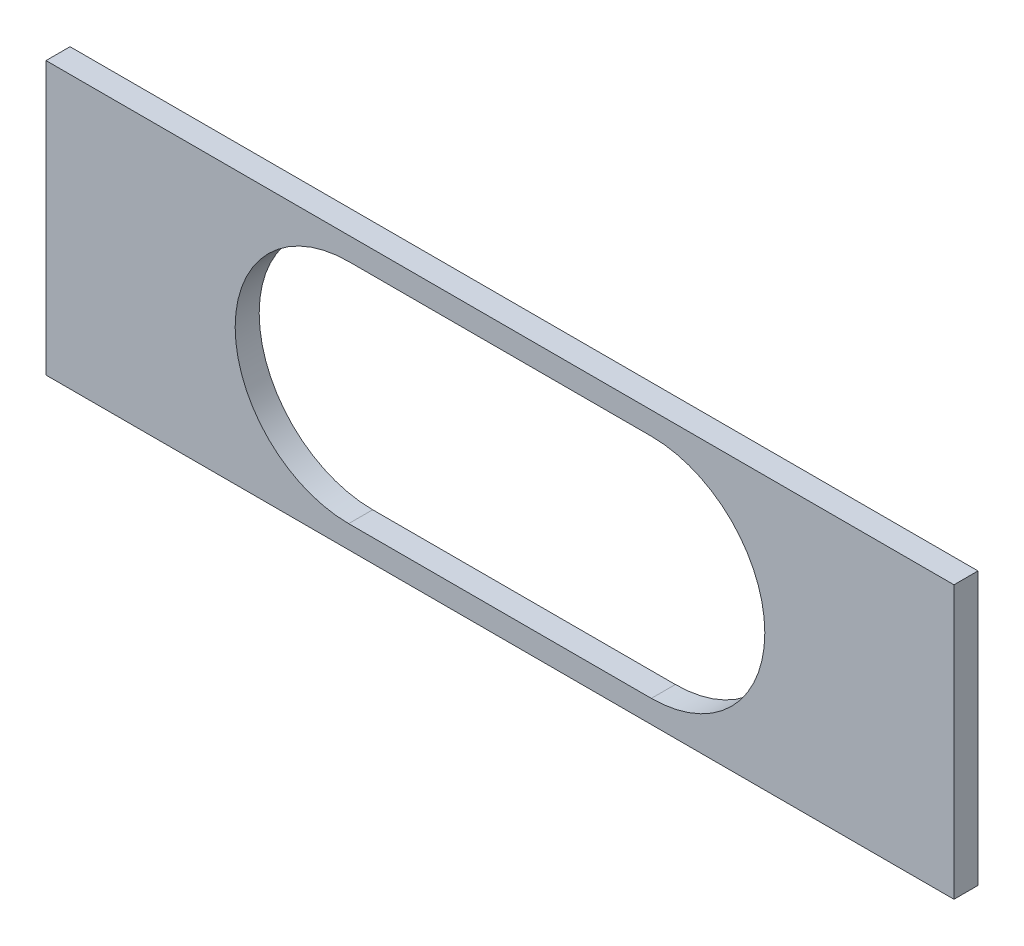
SolidWorks part; units mm, degrees
ref_plane "Front Plane" through (0, 0, 0) normal (0, 0, 1) x (1, 0, 0)
ref_plane "Top Plane" through (0, 0, 0) normal (0, 1, 0) x (1, 0, 0)
ref_plane "Right Plane" through (0, 0, 0) normal (1, 0, 0) x (0, 0, -1)
sketch "Sketch1" plane through (0, 0, 0) normal (0, 0, 1) x (1, 0, 0)
  line L1 (60, -18) -> (-60, -18)
  line L2 (60, -18) -> (60, 18)
  line L3 (60, 18) -> (-60, 18)
  line L4 (-60, -18) -> (-60, 18)
  line L5 (60, -18) -> (-60, 18) construction
  line L6 (60, 18) -> (-60, -18) construction
  point P0 (0, 0)
  dimension "D1" = 120
  dimension "D2" = 36
extrude "Boss-Extrude1" add sketch "Sketch1" along normal blind 3.175
sketch "Sketch2" plane through (0, 0, 3.175) normal (0, 0, 1) x (1, 0, 0)
  line L0 (20, 0) -> (-20, 0) construction
  line L1 (20, -15) -> (-20, -15)
  line L2 (20, 15) -> (-20, 15)
  arc A0 (20, -15) -> (20, 15) centre (20, 0) ccw
  arc A1 (-20, 15) -> (-20, -15) centre (-20, 0) ccw
  point P2 (0, 0)
  dimension "D1" = 40
  dimension "D2" = 30
extrude "Cut-Extrude1" cut sketch "Sketch2" against normal through all
sketch "Sketch4" plane through (0, 0, 0) normal (0, 0, -1) x (-1, 0, 0)
  line L1 (50, -10) -> (-50, -10) construction
  line L2 (50, -10) -> (50, 10) construction
  line L3 (50, 10) -> (-50, 10) construction
  line L4 (-50, -10) -> (-50, 10) construction
  line L5 (50, -10) -> (-50, 10) construction
  line L6 (50, 10) -> (-50, -10) construction
  point P0 (0, 0)
  dimension "D1" = 100
  dimension "D2" = 20
sketch "Sketch5" plane through (0, 0, 0) normal (0, 0, -1) x (-1, 0, 0)
  circle A0 centre (-50, 10) radius 1
  circle A1 centre (-50, -10) radius 1
  circle A2 centre (50, -10) radius 1
  circle A3 centre (50, 10) radius 1
extrude "Cut-Extrude2" cut sketch "Sketch5" against normal blind 0.5
